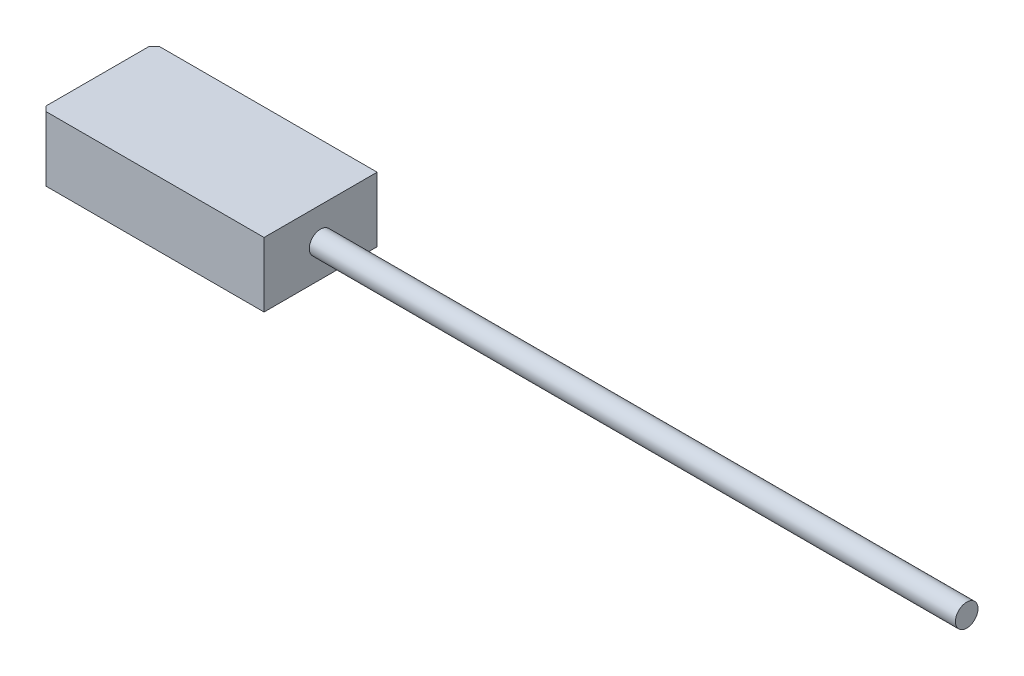
SolidWorks part; units mm, degrees
material "Ductile Iron"
ref_plane "Front Plane" through (0, 0, 0) normal (0, 0, 1) x (1, 0, 0)
ref_plane "Top Plane" through (0, 0, 0) normal (0, 1, 0) x (1, 0, 0)
ref_plane "Right Plane" through (0, 0, 0) normal (1, 0, 0) x (0, 0, -1)
sketch "Sketch1" plane through (0, 0, 0) normal (1, 0, 0) x (0, 0, -1)
  line L1 (-0.35, -0.2) -> (0.35, -0.2)
  line L2 (-0.35, -0.2) -> (-0.35, 0.2)
  line L3 (-0.35, 0.2) -> (0.35, 0.2)
  line L4 (0.35, -0.2) -> (0.35, 0.2)
  line L5 (-0.35, -0.2) -> (0.35, 0.2) construction
  line L6 (-0.35, 0.2) -> (0.35, -0.2) construction
  point P0 (0, 0)
  dimension "D1" = 0.7
  dimension "D2" = 0.4
extrude "Boss-Extrude1" add sketch "Sketch1" along normal blind 1.5
sketch "Sketch2" plane through (1.5, 0, 0) normal (1, 0, 0) x (0, 0, -1)
  circle A0 centre (0, 0) radius 0.07
  dimension "D1" = 0.14
extrude "Boss-Extrude2" add sketch "Sketch2" along normal blind 4
chamfer "Chamfer1" distance 0.12 angle 45 2 edges at (0, -0.2, 0) (0, 0.2, 0)
chamfer "Chamfer2" distance 0.15 angle 45 2 edges at (0, 0, 0.35) (0, 0, -0.35)
